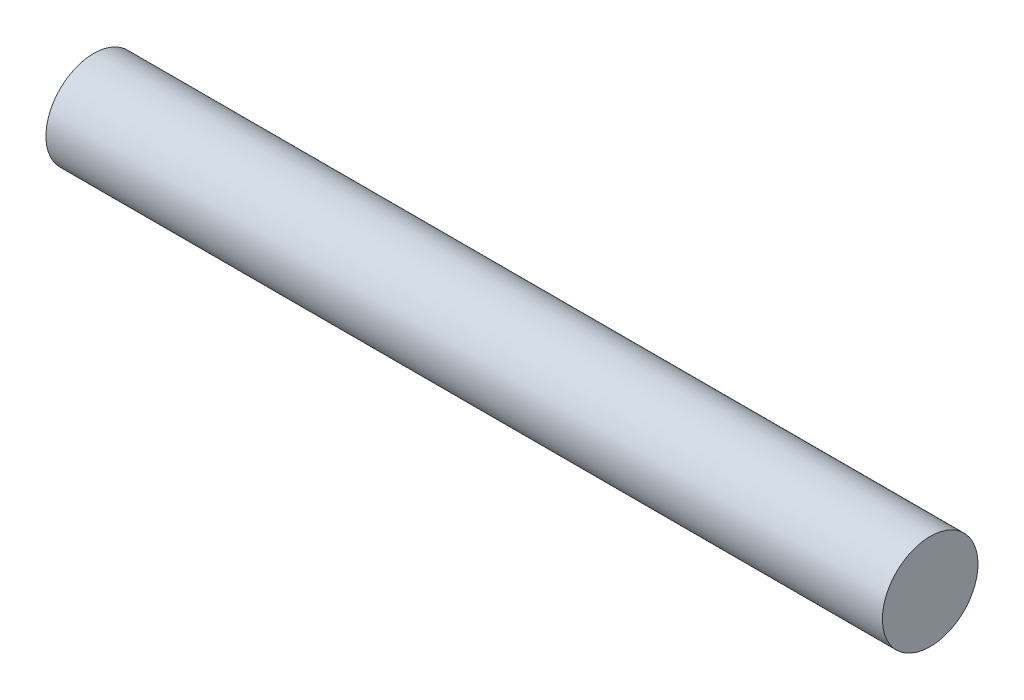
SolidWorks part; units mm, degrees
ref_plane "Front Plane" through (0, 0, 0) normal (0, 0, 1) x (1, 0, 0)
ref_plane "Top Plane" through (0, 0, 0) normal (0, 1, 0) x (1, 0, 0)
ref_plane "Right Plane" through (0, 0, 0) normal (1, 0, 0) x (0, 0, -1)
sketch "Sketch1" plane through (0, 0, 0) normal (1, 0, 0) x (0, 0, -1)
  circle A0 centre (0, 0) radius 4
  dimension "D1" = 8
extrude "Boss-Extrude1" add sketch "Sketch1" along normal blind 70
